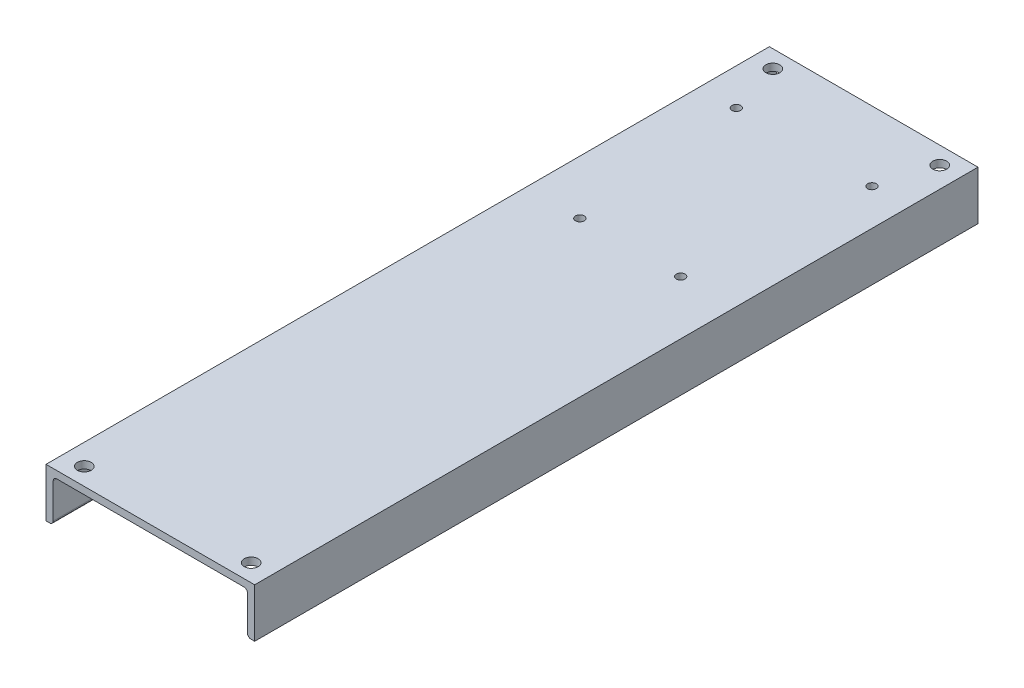
SolidWorks part; units mm, degrees
ref_plane "Front Plane" through (0, 0, 0) normal (0, 0, 1) x (1, 0, 0)
ref_plane "Top Plane" through (0, 0, 0) normal (0, 1, 0) x (1, 0, 0)
ref_plane "Right Plane" through (0, 0, 0) normal (1, 0, 0) x (0, 0, -1)
sketch "Sketch1" plane through (0, 0, 0) normal (0, 0, 1) x (1, 0, 0)
  line L0 (367.792, 0) -> (381, 0)
  line L1 (0, 0) -> (13.208, 0)
  line L2 (0, 0) -> (0, 89.408)
  line L3 (0, 89.408) -> (381, 89.408)
  line L4 (381, 0) -> (381, 89.408)
  line L6 (13.208, 0) -> (13.208, 76.2)
  line L7 (13.208, 76.2) -> (367.792, 76.2)
  line L8 (367.792, 0) -> (367.792, 76.2)
  dimension "D1" = 381
  dimension "D2" = 89.408
  dimension "D3" = 13.208
  dimension "D4" = 13.208
extrude "Boss-Extrude1" add sketch "Sketch1" along normal blind 1320.8
fillet "Fillet1" radius 6.35 4 edges at (13.208, 0, 660.4) (13.208, 76.2, 660.4) (367.792, 76.2, 660.4) (367.792, 0, 660.4)
sketch "Sketch2" plane through (0, 89.408, 0) normal (0, 1, 0) x (1, 0, 0)
  line L0 (190.5, 0) -> (190.5, -1320.8) construction
  line L1 (381, 0) -> (0, 0) construction
  line L2 (381, -1320.8) -> (0, -1320.8) construction
  line L3 (66.675, -127) -> (314.325, -127) construction
  line L4 (98.425, -444.5) -> (282.575, -444.5) construction
  circle A0 centre (66.675, -127) radius 7.9375
  circle A1 centre (314.325, -127) radius 7.9375
  circle A2 centre (98.425, -444.5) radius 7.9375
  circle A3 centre (282.575, -444.5) radius 7.9375
  dimension "D1" = 15.875
  dimension "D2" = 317.5
  dimension "D3" = 127
  dimension "D4" = 247.65
  dimension "D5" = 184.15
extrude "Cut-Extrude1" cut sketch "Sketch2" against normal up to next
sketch "Sketch3" plane through (0, 89.408, 0) normal (0, 1, 0) x (1, 0, 0)
  line L0 (0, -1320.8) -> (0, 0) construction
  line L1 (38.1, -31.75) -> (342.9, -31.75) construction
  line L2 (38.1, -31.75) -> (38.1, -1289.05) construction
  line L3 (38.1, -1289.05) -> (342.9, -1289.05) construction
  line L4 (342.9, -31.75) -> (342.9, -1289.05) construction
  line L5 (381, -1320.8) -> (381, 0) construction
  line L6 (381, 0) -> (0, 0) construction
  line L7 (381, -1320.8) -> (0, -1320.8) construction
  circle A0 centre (38.1, -31.75) radius 12.7
  circle A1 centre (342.9, -31.75) radius 12.7
  circle A2 centre (38.1, -1289.05) radius 12.7
  circle A3 centre (342.9, -1289.05) radius 12.7
  dimension "D5" = 25.4
  dimension "D1" = 38.1
  dimension "D2" = 38.1
  dimension "D3" = 31.75
  dimension "D4" = 31.75
extrude "Cut-Extrude2" cut sketch "Sketch3" against normal up to next
equation "\"D4@Sketch1\"=\"D3@Sketch1\""
equation "\"D2@Sketch3\"=\"D1@Sketch3\""
equation "\"D4@Sketch3\"=\"D3@Sketch3\""
